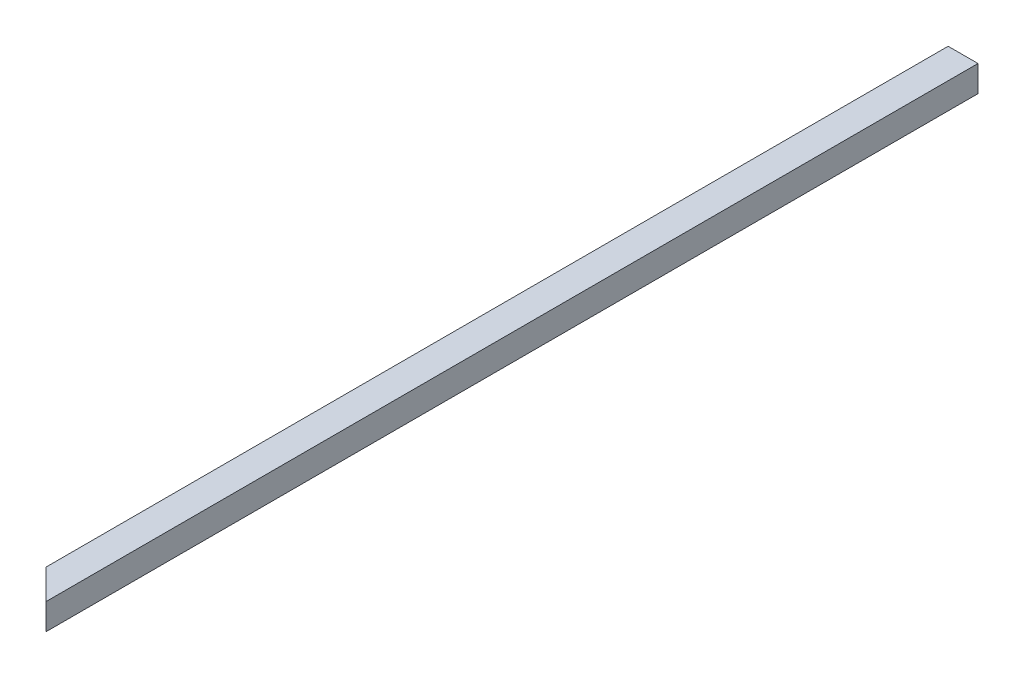
SolidWorks part; units mm, degrees
ref_plane "Alzado" through (0, 0, 0) normal (0, 0, 1) x (1, 0, 0)
ref_plane "Planta" through (0, 0, 0) normal (0, 1, 0) x (1, 0, 0)
ref_plane "Vista lateral" through (0, 0, 0) normal (1, 0, 0) x (0, 0, -1)
sketch "Croquis1" plane through (0, 0, 0) normal (0, 0, 1) x (1, 0, 0)
  line L5 (83.9871, 0) -> (87.9871, 0)
  line L6 (83.9871, 0) -> (83.9871, -3.5)
  line L7 (83.9871, -3.5) -> (87.9871, -3.5)
  line L8 (87.9871, 0) -> (87.9871, -3.5)
extrude "Saliente-Extruir1" add sketch "Croquis1" along normal up to vertex (120.8297 mm away)
sketch "Croquis5" plane through (0, -3.5, 0) normal (0, -1, 0) x (1, 0, 0)
  line L0 (83.9871, 120.8297) -> (87.9871, 124.8297)
  line L1 (87.9871, 124.8297) -> (87.9871, 120.8297)
  line L2 (87.9871, 120.8297) -> (83.9871, 120.8297)
extrude "Saliente-Extruir2" add sketch "Croquis5" against normal up to vertex (3.5 mm away) up to point (83.9871, 0, 120.8297)
